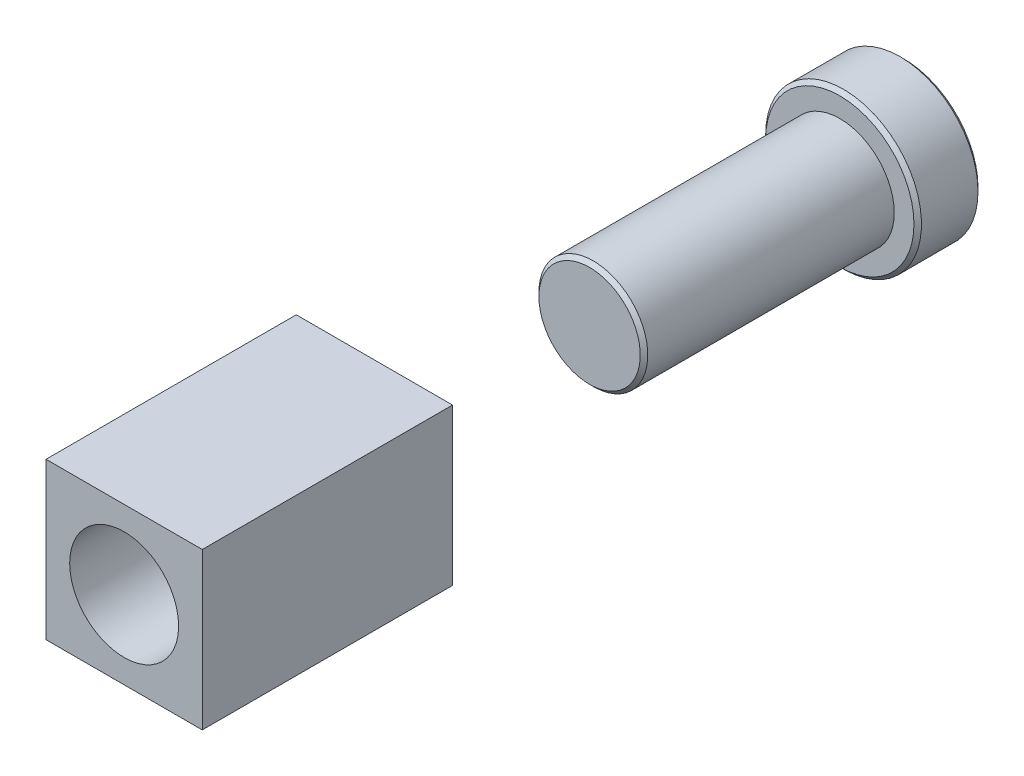
SolidWorks part; units mm, degrees
ref_plane "Front Plane" through (0, 0, 0) normal (0, 0, 1) x (1, 0, 0)
ref_plane "Top Plane" through (0, 0, 0) normal (0, 1, 0) x (1, 0, 0)
ref_plane "Right Plane" through (0, 0, 0) normal (1, 0, 0) x (0, 0, -1)
other "Configuration Table"
sketch "Sketch1" plane through (0, 0, 0) normal (0, 0, 1) x (1, 0, 0)
  circle A0 centre (0, 0) radius 15.8115
  dimension "D1" = 31.623
extrude "Boss-Extrude1" add sketch "Sketch1" along normal blind 12.9988
sketch "Sketch2" plane through (0, 0, 12.9988) normal (0, 0, 1) x (1, 0, 0)
  circle A0 centre (0, 0) radius 11.049
extrude "Boss-Extrude2" add sketch "Sketch2" along normal blind 50.8
ref_plane "Plane1" through (0, 0, 107.4833) normal (0, 0, 1) x (1, 0, 0)
sketch "Sketch3" plane through (0, 0, 107.4833) normal (0, 0, 1) x (1, 0, 0)
  line L0 (15.8613, -15.8613) -> (-15.8613, 15.8613) construction
  line L1 (-15.8613, 15.8613) -> (15.8613, 15.8613)
  line L2 (-15.8613, 15.8613) -> (-15.8613, -15.8613)
  line L3 (-15.8613, -15.8613) -> (15.8613, -15.8613)
  line L4 (15.8613, 15.8613) -> (15.8613, -15.8613)
extrude "Boss-Extrude3" add sketch "Sketch3" along normal blind 50.8 separate body
sketch "Sketch4" plane through (0, 0, 107.4833) normal (0, 0, -1) x (-1, 0, 0)
  circle A0 centre (0, 0) radius 11.0553
  dimension "D1" = 22.1107
extrude "Cut-Extrude1" cut sketch "Sketch4" against normal through all
chamfer "Chamfer1" distance 0.762 angle 45 3 edges at (15.8115, 0, 0) (15.8115, 0, 12.9988) (11.049, 0, 63.7988)
equation "\"Pin Shaft Diameter\" = 0.87"
equation "\"Base Length\"= \"D1@Boss-Extrude3\""
equation "\"D1@Sketch1\"= \"Pin Shaft Diameter\" + 0.375' The pin head diameter is .375 inches bigger than the pin shaft diameter"
equation "\"D1@Boss-Extrude1\"=\"Pin Shaft Diameter\" / 1.7'The pin thickness is proportional to the pin shaft diameter."
equation "\"D1@Boss-Extrude2\"= \"Base Length\"'The pin shaft length is the same as the length of the base boss extrude"
equation "\"D1@Sketch4\"= \"Pin Shaft Diameter\" + 0.0005'The diameter of the base boss extrude requires clearance."
equation "\"D1@Sketch2\"= \"Pin Shaft Diameter\""
equation "\"Chamfer1\"= IIF ( \"Pin Shaft Diameter\" < 1mm , \"suppressed\" , \"unsuppressed\" )"
